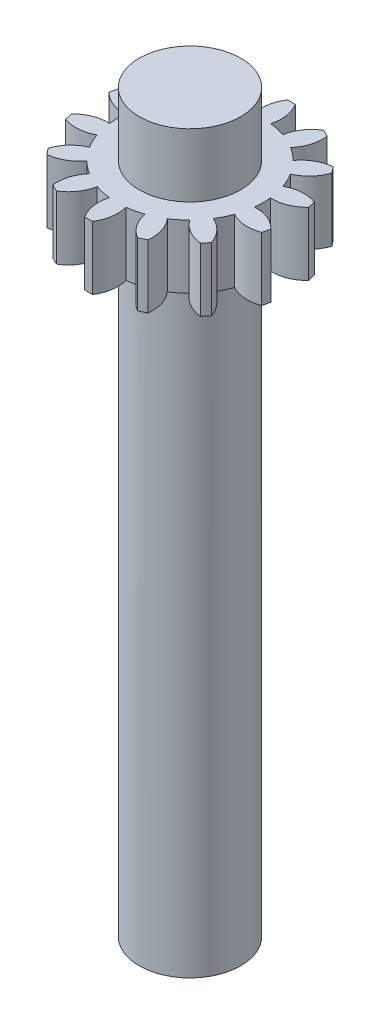
SolidWorks part; units mm, degrees
ref_plane "Front Plane" through (0, 0, 0) normal (0, 0, 1) x (1, 0, 0)
ref_plane "Top Plane" through (0, 0, 0) normal (0, 1, 0) x (1, 0, 0)
ref_plane "Right Plane" through (0, 0, 0) normal (1, 0, 0) x (0, 0, -1)
sketch "Sketch1" plane through (0, 0, 0) normal (0, 1, 0) x (1, 0, 0)
  circle A0 centre (0, 0) radius 0.4
  arc A1 (3.7449, -7.0694) -> (3.0719, -4.8595) centre (0.9684, -6.7075) ccw
  arc A2 (3.0719, -4.8595) -> (4.0541, -4.0762) centre (0, 0) ccw
  arc A3 (4.0541, -4.0762) -> (6.0588, -5.2241) centre (6.3238, -2.4367) ccw
  arc A4 (6.0588, -5.2241) -> (6.4413, -4.7444) centre (0, 0) ccw
  arc A5 (6.4413, -4.7444) -> (4.8761, -3.0454) centre (3.7828, -5.6231) ccw
  arc A6 (4.8761, -3.0454) -> (5.4212, -1.9136) centre (0, 0) ccw
  arc A7 (5.4212, -1.9136) -> (7.7254, -2.0779) centre (6.7548, 0.5485) ccw
  arc A8 (7.7254, -2.0779) -> (7.8619, -1.4798) centre (0, 0) ccw
  arc A9 (7.8619, -1.4798) -> (5.7146, -0.6281) centre (5.8479, -3.4249) ccw
  arc A10 (5.7146, -0.6281) -> (5.7146, 0.6281) centre (0, 0) ccw
  arc A11 (5.7146, 0.6281) -> (7.8619, 1.4798) centre (5.8479, 3.4249) ccw
  arc A12 (7.8619, 1.4798) -> (7.7254, 2.0779) centre (0, 0) ccw
  arc A13 (7.7254, 2.0779) -> (5.4212, 1.9136) centre (6.7548, -0.5485) ccw
  arc A14 (5.4212, 1.9136) -> (4.8761, 3.0454) centre (0, 0) ccw
  arc A15 (4.8761, 3.0454) -> (6.4413, 4.7444) centre (3.7828, 5.6231) ccw
  arc A16 (6.4413, 4.7444) -> (6.0588, 5.2241) centre (0, 0) ccw
  arc A17 (6.0588, 5.2241) -> (4.0541, 4.0762) centre (6.3238, 2.4367) ccw
  arc A18 (4.0541, 4.0762) -> (3.0719, 4.8595) centre (0, 0) ccw
  arc A19 (3.0719, 4.8595) -> (3.7449, 7.0694) centre (0.9684, 6.7075) ccw
  arc A20 (3.7449, 7.0694) -> (3.1921, 7.3355) centre (0, 0) ccw
  arc A21 (3.1921, 7.3355) -> (1.884, 5.4315) centre (4.6404, 4.9392) ccw
  arc A22 (1.884, 5.4315) -> (0.6592, 5.7111) centre (0, 0) ccw
  arc A23 (0.6592, 5.7111) -> (0.3068, 7.9941) centre (-2.0378, 6.4634) ccw
  arc A24 (0.3068, 7.9941) -> (-0.3068, 7.9941) centre (0, 0) ccw
  arc A25 (-0.3068, 7.9941) -> (-0.6592, 5.7111) centre (2.0378, 6.4634) ccw
  arc A26 (-0.6592, 5.7111) -> (-1.884, 5.4315) centre (0, 0) ccw
  arc A27 (-1.884, 5.4315) -> (-3.1921, 7.3355) centre (-4.6404, 4.9392) ccw
  arc A28 (-3.1921, 7.3355) -> (-3.7449, 7.0694) centre (0, 0) ccw
  arc A29 (-3.7449, 7.0694) -> (-3.0719, 4.8595) centre (-0.9684, 6.7075) ccw
  arc A30 (-3.0719, 4.8595) -> (-4.0541, 4.0762) centre (0, 0) ccw
  arc A31 (-4.0541, 4.0762) -> (-6.0588, 5.2241) centre (-6.3238, 2.4367) ccw
  arc A32 (-6.0588, 5.2241) -> (-6.4413, 4.7444) centre (0, 0) ccw
  arc A33 (-6.4413, 4.7444) -> (-4.8761, 3.0454) centre (-3.7828, 5.6231) ccw
  arc A34 (-4.8761, 3.0454) -> (-5.4212, 1.9136) centre (0, 0) ccw
  arc A35 (-5.4212, 1.9136) -> (-7.7254, 2.0779) centre (-6.7548, -0.5485) ccw
  arc A36 (-7.7254, 2.0779) -> (-7.8619, 1.4798) centre (0, 0) ccw
  arc A37 (-7.8619, 1.4798) -> (-5.7146, 0.6281) centre (-5.8479, 3.4249) ccw
  arc A38 (-5.7146, 0.6281) -> (-5.7146, -0.6281) centre (0, 0) ccw
  arc A39 (-5.7146, -0.6281) -> (-7.8619, -1.4798) centre (-5.8479, -3.4249) ccw
  arc A40 (-7.8619, -1.4798) -> (-7.7254, -2.0779) centre (0, 0) ccw
  arc A41 (-7.7254, -2.0779) -> (-5.4212, -1.9136) centre (-6.7548, 0.5485) ccw
  arc A42 (-5.4212, -1.9136) -> (-4.8761, -3.0454) centre (0, 0) ccw
  arc A43 (-4.8761, -3.0454) -> (-6.4413, -4.7444) centre (-3.7828, -5.6231) ccw
  arc A44 (-6.4413, -4.7444) -> (-6.0588, -5.2241) centre (0, 0) ccw
  arc A45 (-6.0588, -5.2241) -> (-4.0541, -4.0762) centre (-6.3238, -2.4367) ccw
  arc A46 (-4.0541, -4.0762) -> (-3.0719, -4.8595) centre (0, 0) ccw
  arc A47 (-3.0719, -4.8595) -> (-3.7449, -7.0694) centre (-0.9684, -6.7075) ccw
  arc A48 (-3.7449, -7.0694) -> (-3.1921, -7.3355) centre (0, 0) ccw
  arc A49 (-3.1921, -7.3355) -> (-1.884, -5.4315) centre (-4.6404, -4.9392) ccw
  arc A50 (-1.884, -5.4315) -> (-0.6592, -5.7111) centre (0, 0) ccw
  arc A51 (-0.6592, -5.7111) -> (-0.3068, -7.9941) centre (2.0378, -6.4634) ccw
  arc A52 (-0.3068, -7.9941) -> (0.3068, -7.9941) centre (0, 0) ccw
  arc A53 (0.3068, -7.9941) -> (0.6592, -5.7111) centre (-2.0378, -6.4634) ccw
  arc A54 (0.6592, -5.7111) -> (1.884, -5.4315) centre (0, 0) ccw
  arc A55 (1.884, -5.4315) -> (3.1921, -7.3355) centre (4.6404, -4.9392) ccw
  arc A56 (3.1921, -7.3355) -> (3.7449, -7.0694) centre (0, 0) ccw
extrude "Boss-Extrude1" add sketch "Sketch1" against normal blind 5
sketch "Sketch2" plane through (0, -5, 0) normal (0, -1, 0) x (1, 0, 0)
  circle A0 centre (0, 0) radius 4
  dimension "D1" = 8
extrude "Boss-Extrude2" add sketch "Sketch2" along normal blind 48 and the other way up to surface (5 mm away) other way up to face at (0, 0, -0.4)
sketch "Sketch3" plane through (0, 0, 0) normal (0, 1, 0) x (1, 0, 0)
  circle A0 centre (0, 0) radius 4
  dimension "D1" = 8
extrude "Boss-Extrude3" add sketch "Sketch3" along normal blind 5
sketch "Sketch4" plane through (0, -53, 0) normal (0, -1, 0) x (1, 0, 0)
  line L0 (-2.5, 0) -> (2.5, 0) construction
  line L1 (-2, -1.5) -> (2, -1.5)
  line L2 (-2, 1.5) -> (2, 1.5)
  line L3 (-2.5, 1.5) -> (2.5, 1.5) construction
  line L4 (-2.5, -1.5) -> (2.5, -1.5) construction
  arc A0 (-2, 1.5) -> (-2, -1.5) centre (0, 0) ccw
  arc A1 (2, -1.5) -> (2, 1.5) centre (0, 0) ccw
  point P6 (0, 0)
  dimension "D1" = 5
  dimension "D2" = 1.5
  dimension "D3" = 1.5
extrude "Cut-Extrude1" cut sketch "Sketch4" against normal up to surface (48 mm away) up to face at (0, -5, 4)
